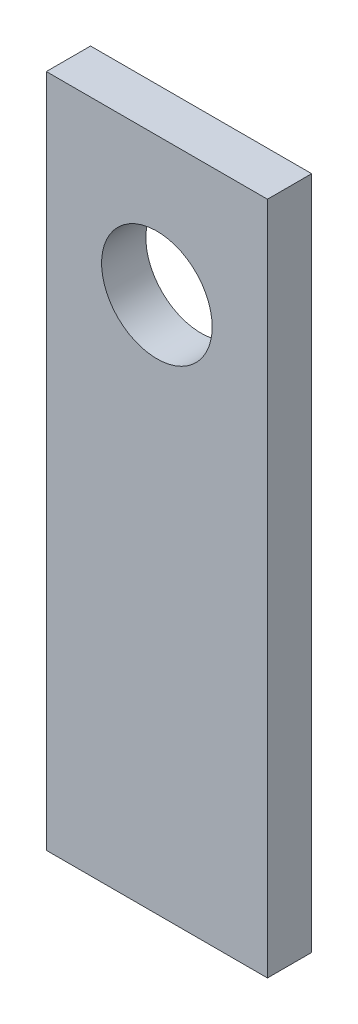
SolidWorks part; units mm, degrees
ref_plane "Piano frontale" through (0, 0, 0) normal (0, 0, 1) x (1, 0, 0)
ref_plane "Piano superiore" through (0, 0, 0) normal (0, 1, 0) x (1, 0, 0)
ref_plane "Piano destro" through (0, 0, 0) normal (1, 0, 0) x (0, 0, -1)
sketch "Schizzo1" plane through (0, 0, 0) normal (0, 0, 1) x (1, 0, 0)
  line L1 (-10, 30.5) -> (10, 30.5)
  line L2 (-10, 30.5) -> (-10, -30.5)
  line L3 (-10, -30.5) -> (10, -30.5)
  line L4 (10, 30.5) -> (10, -30.5)
  line L5 (-10, 30.5) -> (10, -30.5) construction
  line L6 (-10, -30.5) -> (10, 30.5) construction
  point P0 (0, 0)
  dimension "D1" = 20
  dimension "D2" = 61
extrude "Estrusione-Estrusione1" add sketch "Schizzo1" along normal blind 4
sketch "Schizzo2" plane through (0, 0, 4) normal (0, 0, 1) x (1, 0, 0)
  line L0 (10, 30.5) -> (-10, 30.5) construction
  circle A0 centre (0, 18) radius 5
  dimension "D1" = 10
  dimension "D2" = 12.5
extrude "Taglio-Estrusione1" cut sketch "Schizzo2" against normal blind 4
hole_wizard "Foro per Vite M2-2" positions "Schizzo11" profile "Schizzo12" hole size "M2" standard "ISO"
sketch "Schizzo11" plane through (0, -30.5, 0) normal (0, -1, 0) x (-1, 0, 0)
  line L0 (0, 0) -> (0, -4) construction
  line L1 (10, 0) -> (-10, 0) construction
  line L2 (10, -4) -> (-10, -4) construction
  line L4 (10, -2) -> (-10, -2) construction
  line L5 (10, -4) -> (10, 0) construction
  line L6 (-10, -4) -> (-10, 0) construction
  point P0 (5, -2)
  point P2 (-5, -2)
  point P22 (0, 0)
  point P23 (0, -2)
  dimension "D1" = 5
sketch "Schizzo12" plane through (-5, -30.5, 2) normal (1, 0, 0) x (0, 0, -1)
  line L0 (0, 0) -> (0, 4)
  line L1 (0, 4) -> (1.2, 4)
  line L2 (1.2, 4) -> (1.2, 0)
  line L5 (1.2, 0) -> (0, 0)
  line L10 (0, 4) -> (-1.2, 4) construction
  line L11 (0, -6.35) -> (0, 107.95) construction
  dimension "Hole Dia." = 2.4
  dimension "Hole Depth" = 4
  dimension "Drill Angle" = 180
